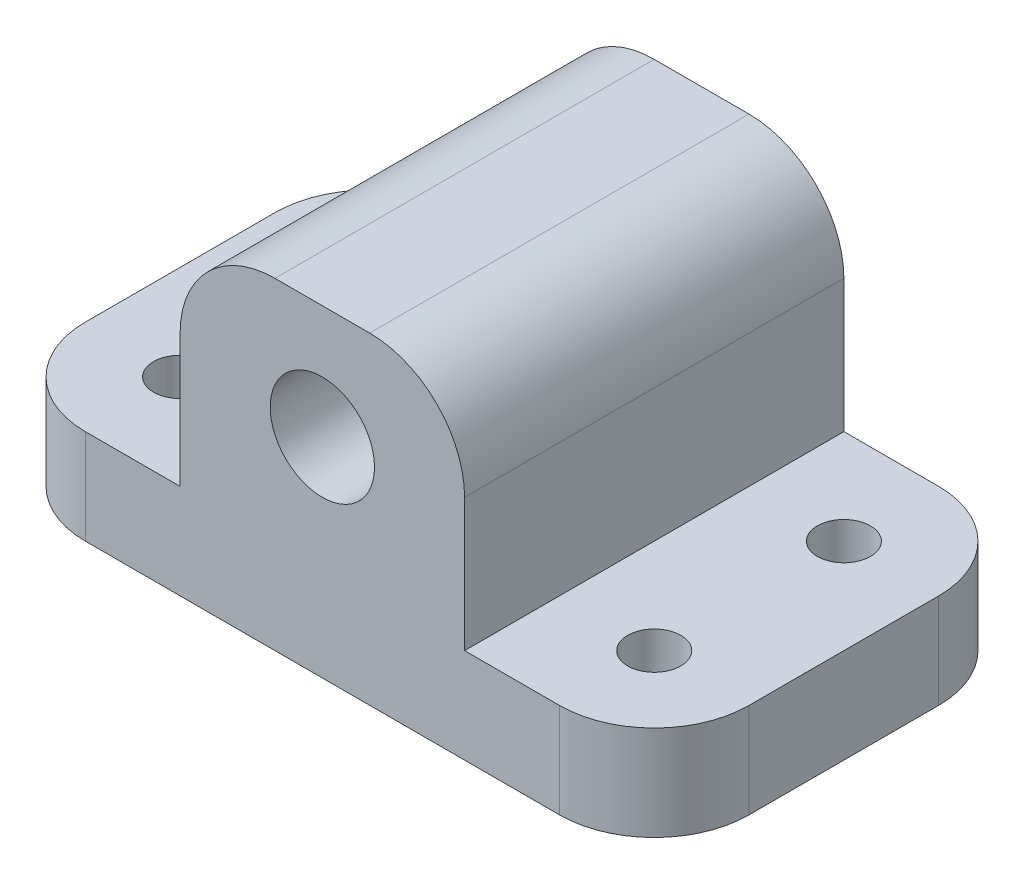
SolidWorks part; units mm, degrees
material "ABS"
ref_plane "Front Plane" through (0, 0, 0) normal (0, 0, 1) x (1, 0, 0)
ref_plane "Top Plane" through (0, 0, 0) normal (0, 1, 0) x (1, 0, 0)
ref_plane "Right Plane" through (0, 0, 0) normal (1, 0, 0) x (0, 0, -1)
sketch "Sketch1" plane through (0, 0, 0) normal (0, 0, 1) x (1, 0, 0)
  line L0 (0, 0) -> (44.45, 0)
  line L1 (44.45, 0) -> (44.45, 6.35)
  line L2 (44.45, 6.35) -> (31.75, 6.35)
  line L3 (31.75, 6.35) -> (31.75, 21.59)
  line L4 (31.75, 21.59) -> (12.7, 21.59)
  line L5 (12.7, 21.59) -> (12.7, 6.35)
  line L6 (12.7, 6.35) -> (0, 6.35)
  line L7 (0, 6.35) -> (0, 0)
  circle A0 centre (22.225, 13.97) radius 3.4925
  dimension "D5" = 6.985
  dimension "D1" = 44.45
  dimension "D2" = 19.05
  dimension "D3" = 6.35
  dimension "D4" = 15.24
  dimension "D6" = 7.62
  dimension "D7" = 9.525
extrude "Boss-Extrude1" add sketch "Sketch1" along normal blind 25.4
sketch "Sketch2" plane through (0, 6.35, 0) normal (0, 1, 0) x (1, 0, 0)
  line L0 (0, -25.4) -> (0, 0) construction
  line L1 (12.7, -25.4) -> (0, -25.4) construction
  line L2 (12.7, 0) -> (0, 0) construction
  line L3 (6.35, -6.35) -> (6.35, 0) construction
  line L5 (6.35, -19.05) -> (6.35, -25.4) construction
  line L7 (38.1, -6.35) -> (44.45, -6.35) construction
  line L8 (44.45, -25.4) -> (44.45, 0) construction
  line L9 (6.35, -6.35) -> (0, -6.35) construction
  circle A0 centre (6.35, -6.35) radius 1.778
  circle A1 centre (6.35, -19.05) radius 1.778
  circle A2 centre (38.1, -6.35) radius 1.778
  circle A3 centre (38.1, -19.05) radius 1.778
  point P10 (0, 0)
  dimension "D4" = 3.556
  dimension "D1" = 6.35
  dimension "D3" = 6.35
extrude "Cut-Extrude1" cut sketch "Sketch2" against normal through all
fillet "Fillet2" radius 6.35 2 edges at (31.75, 21.59, 12.7) (12.7, 21.59, 12.7)
fillet "Fillet1" radius 6.35 4 edges at (0, 3.175, 0) (44.45, 3.175, 0) (44.45, 3.175, 25.4) (0, 3.175, 25.4)
